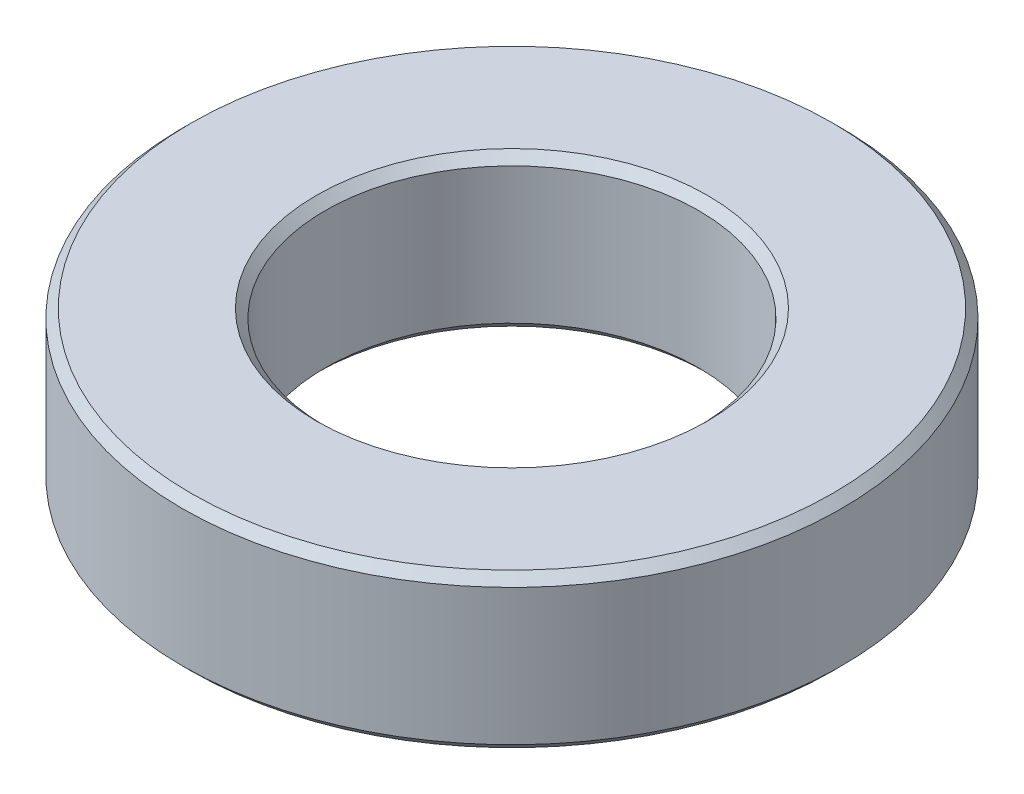
SolidWorks part; units mm, degrees
material "Chrome Stainless Steel"
ref_plane "Front Plane" through (0, 0, 0) normal (0, 0, 1) x (1, 0, 0)
ref_plane "Top Plane" through (0, 0, 0) normal (0, 1, 0) x (1, 0, 0)
ref_plane "Right Plane" through (0, 0, 0) normal (1, 0, 0) x (0, 0, -1)
sketch "Sketch1" plane through (0, 0, 0) normal (0, 1, 0) x (1, 0, 0)
  circle A0 centre (0, 0) radius 8.5
  circle A1 centre (0, 0) radius 15
  dimension "D1" = 17
  dimension "D2" = 30
extrude "Boss-Extrude1" add sketch "Sketch1" along normal blind 7
chamfer "Chamfer1" distance 0.4 angle 45 4 edges at (0, 0, 8.5) (0, 7, 8.5) (0, 0, 15) (0, 7, 15)
